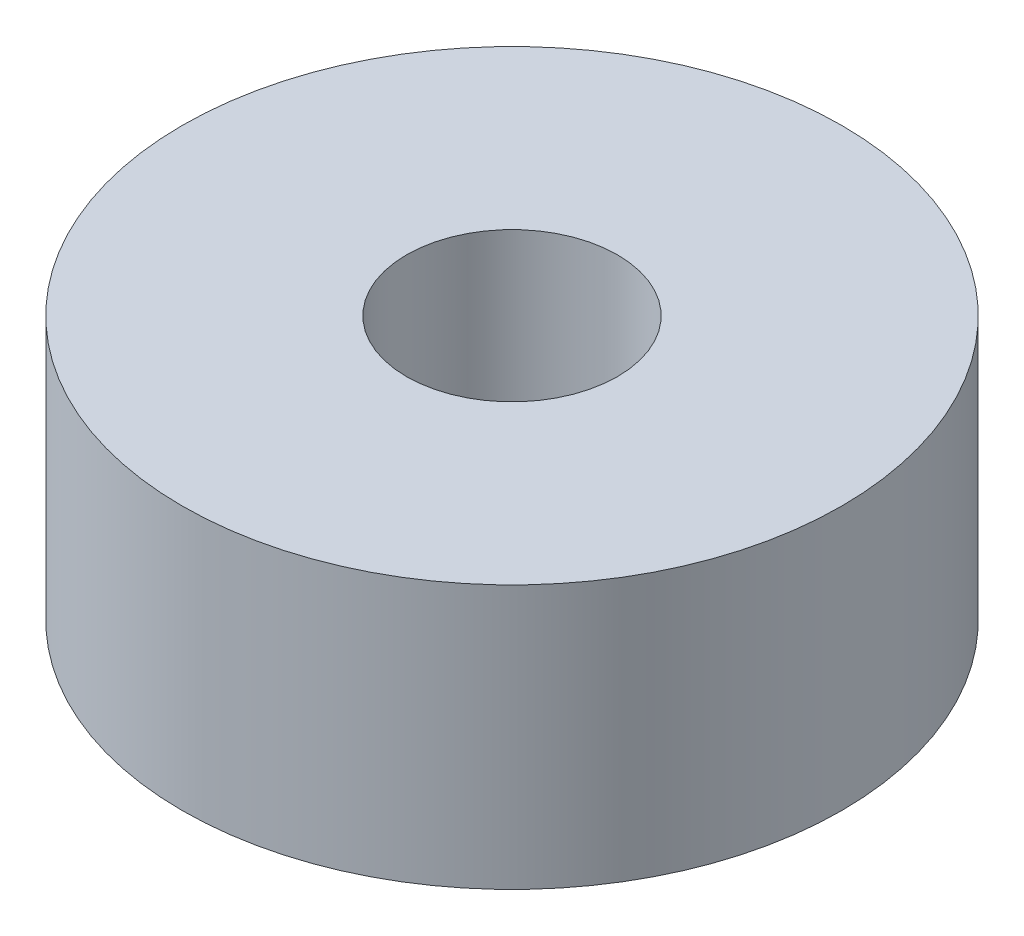
SolidWorks part; units mm, degrees
ref_plane "Front Plane" through (0, 0, 0) normal (0, 0, 1) x (1, 0, 0)
ref_plane "Top Plane" through (0, 0, 0) normal (0, 1, 0) x (1, 0, 0)
ref_plane "Right Plane" through (0, 0, 0) normal (1, 0, 0) x (0, 0, -1)
sketch "Sketch1" plane through (0, 0, 0) normal (0, 1, 0) x (1, 0, 0)
  circle A0 centre (0, 0) radius 4
  circle A1 centre (0, 0) radius 12.5
  dimension "D1" = 8
  dimension "D2" = 25
extrude "Boss-Extrude1" add sketch "Sketch1" along normal blind 10
